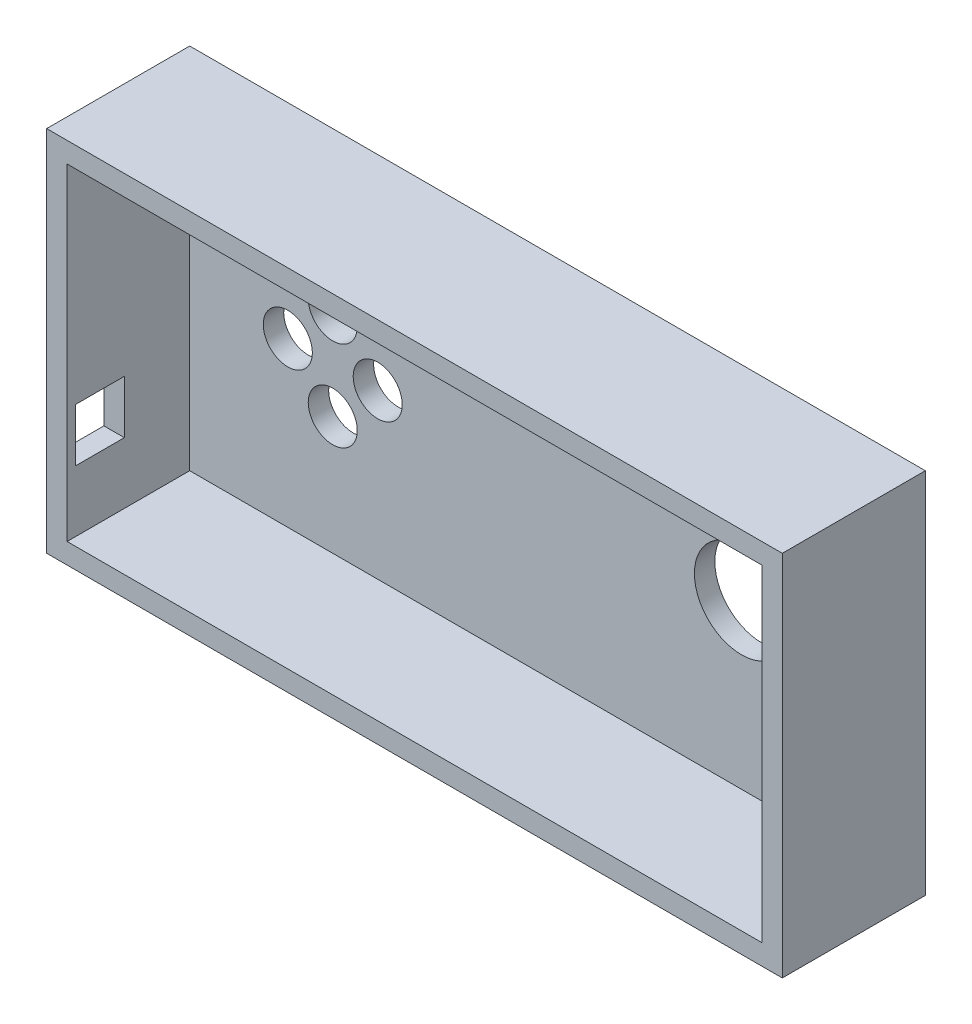
SolidWorks part; units mm, degrees
ref_plane "Plan de face" through (0, 0, 0) normal (0, 0, 1) x (1, 0, 0)
ref_plane "Plan de dessus" through (0, 0, 0) normal (0, 1, 0) x (1, 0, 0)
ref_plane "Plan de droite" through (0, 0, 0) normal (1, 0, 0) x (0, 0, -1)
sketch "Esquisse1" plane through (0, 0, 0) normal (0, 0, 1) x (1, 0, 0)
  line L1 (0, 0) -> (180, 0)
  line L2 (0, 0) -> (0, 90)
  line L3 (0, 90) -> (180, 90)
  line L4 (180, 0) -> (180, 90)
  dimension "D1" = 180
  dimension "D2" = 90
extrude "Boss.-Extru.1" add sketch "Esquisse1" along normal blind 5
sketch "Esquisse2" plane through (0, 0, 5) normal (0, 0, 1) x (1, 0, 0)
  line L8 (5, 85) -> (5, 5)
  line L9 (5, 5) -> (175, 5)
  line L10 (175, 5) -> (175, 85)
  line L11 (175, 85) -> (5, 85)
  line L12 (5, 85) -> (5, 5)
  line L13 (5, 5) -> (175, 5)
  line L14 (175, 5) -> (175, 85)
  line L15 (175, 85) -> (5, 85)
  line M5 (0, 90) -> (0, 0)
  line M6 (0, 0) -> (180, 0)
  line M7 (180, 0) -> (180, 90)
  line M8 (180, 90) -> (0, 90)
  dimension "D1" = 5
extrude "Boss.-Extru.2" add sketch "Esquisse2" along normal blind 30 contours L15 L14 L13 L12 M8 M5 M6 M7
sketch "Esquisse3" plane through (0, 0, 0) normal (0, 0, -1) x (-1, 0, 0)
  line L0 (-40, 90) -> (-40, 0) construction
  line L1 (-180, 90) -> (0, 90) construction
  line L2 (0, 0) -> (-180, 0) construction
  line L3 (-180, 45) -> (0, 45) construction
  line L4 (-180, 0) -> (-180, 90) construction
  line L5 (0, 90) -> (0, 0) construction
  circle A0 centre (-140, 45) radius 11.5
  circle A1 centre (-40, 56) radius 6
  circle A3 centre (-40, 34) radius 6
  circle A4 centre (-51, 45) radius 6
  circle A5 centre (-29, 45) radius 6
  dimension "D1" = 23
  dimension "D2" = 12
  dimension "D3" = 12
  dimension "D4" = 12
  dimension "D5" = 12
  dimension "D6" = 0
  dimension "D7" = 0
  dimension "D8" = 0
  dimension "D9" = 22
  dimension "D10" = 11
  dimension "D12" = 22
  dimension "D14" = 11
  dimension "D15" = 40
  dimension "D16" = 40
extrude "Enlèv. mat.-Extru.1" cut sketch "Esquisse3" against normal up to surface (5 mm away) up to face at (90, 45, 5)
sketch "Esquisse4" plane through (0, 0, 0) normal (-1, 0, 0) x (0, 0, 1)
  line L0 (35, 0) -> (0, 0) construction
  line L1 (21, 20) -> (33, 20)
  line L2 (21, 20) -> (21, 33)
  line L3 (21, 33) -> (33, 33)
  line L4 (33, 20) -> (33, 33)
  line L5 (35, 90) -> (35, 0) construction
  dimension "D1" = 20
  dimension "D2" = 13
  dimension "D3" = 12
  dimension "D4" = 2
extrude "Enlèv. mat.-Extru.2" cut sketch "Esquisse4" against normal up to surface (5 mm away) up to face at (5, 45, 20)
